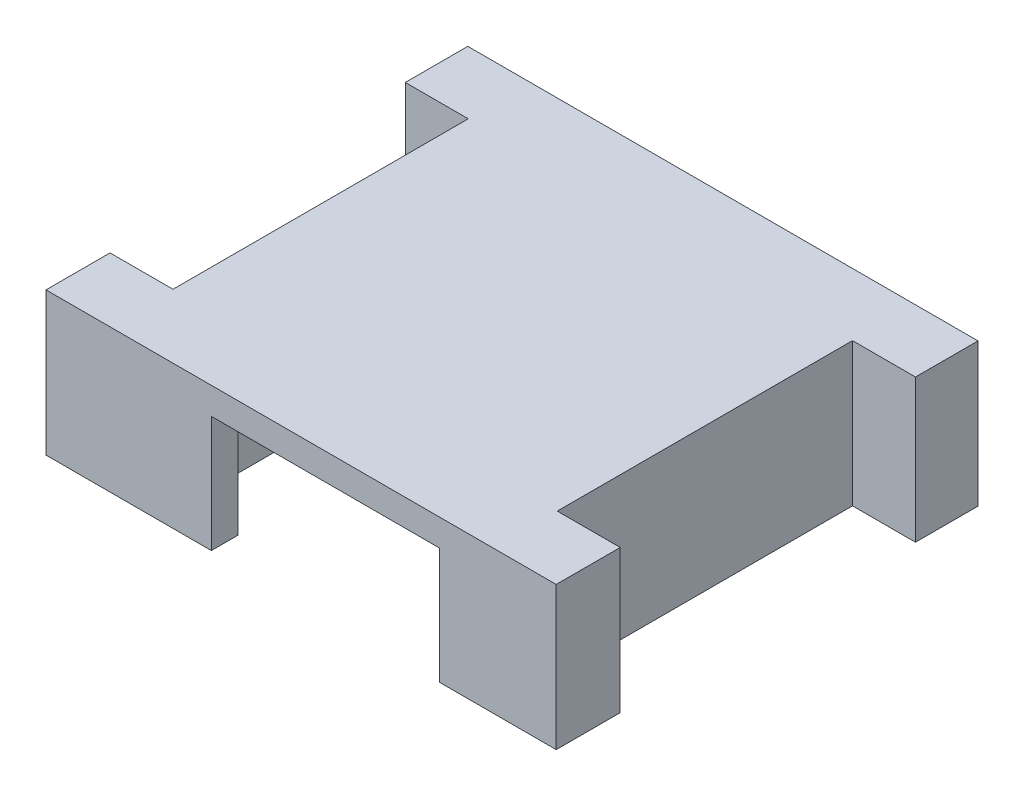
SolidWorks part; units mm, degrees
ref_plane "Front Plane" through (0, 0, 0) normal (0, 0, 1) x (1, 0, 0)
ref_plane "Top Plane" through (0, 0, 0) normal (0, 1, 0) x (1, 0, 0)
ref_plane "Right Plane" through (0, 0, 0) normal (1, 0, 0) x (0, 0, -1)
sketch "Sketch1" plane through (0, 0, 0) normal (0, 1, 0) x (1, 0, 0)
  line L0 (-20.255, 23.58) -> (20.255, 23.58)
  line L1 (-17.255, -20.58) -> (17.255, -20.58)
  line L2 (-17.255, -20.58) -> (-17.255, 20.58)
  line L3 (-17.255, 20.58) -> (17.255, 20.58)
  line L4 (17.255, -20.58) -> (17.255, 20.58)
  line L5 (-17.255, -20.58) -> (17.255, 20.58) construction
  line L6 (-17.255, 20.58) -> (17.255, -20.58) construction
  line L7 (20.255, -23.4108) -> (20.255, 23.58)
  line L8 (-20.255, -23.58) -> (20.255, -23.58)
  line L9 (-20.255, -23.58) -> (-20.255, 23.58)
  line L10 (-11.255, 23.58) -> (-11.255, 20.58)
  line L11 (14.255, 23.58) -> (14.255, 20.58)
  line L12 (-11.255, -20.58) -> (-11.255, -23.58)
  line L13 (14.255, -20.58) -> (14.255, -23.58)
  line L14 (20.255, -23.58) -> (20.255, 23.58) construction
  line L15 (-22.7039, 23.58) -> (-20.255, 23.58)
  line L16 (-22.7039, 23.58) -> (-22.7039, -23.4108)
  line L17 (-22.7039, -23.58) -> (-20.255, -23.58)
  line L18 (-20.255, 23.58) -> (-20.255, -23.58)
  line L19 (-29.745, -23.4108) -> (-22.7039, -23.4108)
  line L20 (-29.745, -23.4108) -> (-29.745, -23.58)
  line L21 (-29.745, -23.58) -> (-22.7039, -23.58)
  line L23 (27.2961, -23.4108) -> (20.255, -23.4108)
  line L24 (27.2961, -23.4108) -> (27.2961, -23.58)
  line L25 (27.2961, -23.58) -> (20.255, -23.58)
  point P0 (0, 0)
  line B0 (20.255, 23.58) -> (27.2961, 23.58)
  line B1 (20.255, 23.58) -> (20.255, 16.5892)
  line B2 (20.255, 16.5892) -> (27.2961, 16.5892)
  line B3 (27.2961, 23.58) -> (27.2961, 16.5892)
  circle B4 centre (23.7755, 20.0846) radius 1.35
  line B5 (-29.745, 23.58) -> (-22.7039, 23.58)
  line B6 (-29.745, 23.58) -> (-29.745, 16.5892)
  line B7 (-29.745, 16.5892) -> (-22.7039, 16.5892)
  line B8 (-22.7039, 23.58) -> (-22.7039, 16.5892)
  circle B9 centre (-26.2245, 20.0846) radius 1.35
  line B10 (-29.745, -16.42) -> (-22.7039, -16.42)
  line B11 (-29.745, -16.42) -> (-29.745, -23.4108)
  line B12 (-29.745, -23.4108) -> (-22.7039, -23.4108)
  line B13 (-22.7039, -16.42) -> (-22.7039, -23.4108)
  circle B14 centre (-26.2245, -19.9154) radius 1.35
  line B15 (20.255, -16.42) -> (27.2961, -16.42)
  line B16 (20.255, -16.42) -> (20.255, -23.4108)
  line B17 (20.255, -23.4108) -> (27.2961, -23.4108)
  line B18 (27.2961, -16.42) -> (27.2961, -23.4108)
  circle B19 centre (23.7755, -19.9154) radius 1.35
  dimension "D6" = 2
  dimension "D1" = 34.51
  dimension "D2" = 41.16
  dimension "D4" = 3
  dimension "D5" = 6
  dimension "D7" = 2
  dimension "D3" = 3
sketch_block_instance "Block1-1"
sketch_block "Block1" parameters "D1"=2.7
sketch_block_instance "Block1-3"
sketch_block_instance "Block1-4"
sketch_block_instance "Block1-5"
extrude "Boss-Extrude2" add sketch "Sketch1" along normal blind 13 contours L12 L1 L2 L3 L10 L0 L9 L8 | L1 L13 L8 L7 L0 L11 L3 L4 | B6 B7 L16 B5 B9 | L16 L17 L9 L15 | B11 B12 L16 B10 B14 | B18 B15 L7 B17 B19 | B3 B0 L7 B2 B4
sketch "Sketch4" plane through (0, 13, 0) normal (0, 1, 0) x (1, 0, 0)
  line L1 (-29.745, 23.58) -> (27.2961, 23.58)
  line L2 (-29.745, 23.58) -> (-29.745, -23.58)
  line L3 (-29.745, -23.58) -> (27.2961, -23.58)
  line L4 (27.2961, 23.58) -> (27.2961, -23.58)
  line L5 (20.255, 16.5892) -> (27.2961, 16.5892)
  line L6 (20.255, 16.5892) -> (20.255, -16.42)
  line L7 (20.255, -16.42) -> (27.2961, -16.42)
  line L8 (27.2961, 16.5892) -> (27.2961, -16.42)
  line L9 (-22.7039, 16.5892) -> (-29.745, 16.5892)
  line L10 (-22.7039, 16.5892) -> (-22.7039, -16.42)
  line L11 (-22.7039, -16.42) -> (-29.745, -16.42)
  line L12 (-29.745, 16.5892) -> (-29.745, -16.42)
  line M9 (-11.255, -23.58) -> (-11.255, -20.58)
  line M10 (-11.255, -20.58) -> (-17.255, -20.58)
  line M11 (-17.255, -20.58) -> (-17.255, 20.58)
  line M12 (-17.255, 20.58) -> (-11.255, 20.58)
  line M13 (-11.255, 20.58) -> (-11.255, 23.58)
  line M14 (-11.255, 23.58) -> (-29.745, 23.58)
  line M15 (-29.745, 23.58) -> (-29.745, 16.5892)
  line M16 (-29.745, 16.5892) -> (-22.7039, 16.5892)
  line M17 (-22.7039, 16.5892) -> (-22.7039, -16.42)
  line M18 (-22.7039, -16.42) -> (-29.745, -16.42)
  line M19 (-29.745, -16.42) -> (-29.745, -23.58)
  line M20 (-29.745, -23.58) -> (-11.255, -23.58)
  circle M21 centre (-26.2245, -19.9154) radius 1.35
  circle M22 centre (-26.2245, 20.0846) radius 1.35
extrude "Boss-Extrude5" add sketch "Sketch4" along normal blind 3 contours M20 M9 M10 M11 M12 M13 M14 M15 M16 M17 M18 M19 M21 M22 | L7 L6 L5 L4 L1 L3 M13 M12 M11 M10 M9 | M22 | M21
